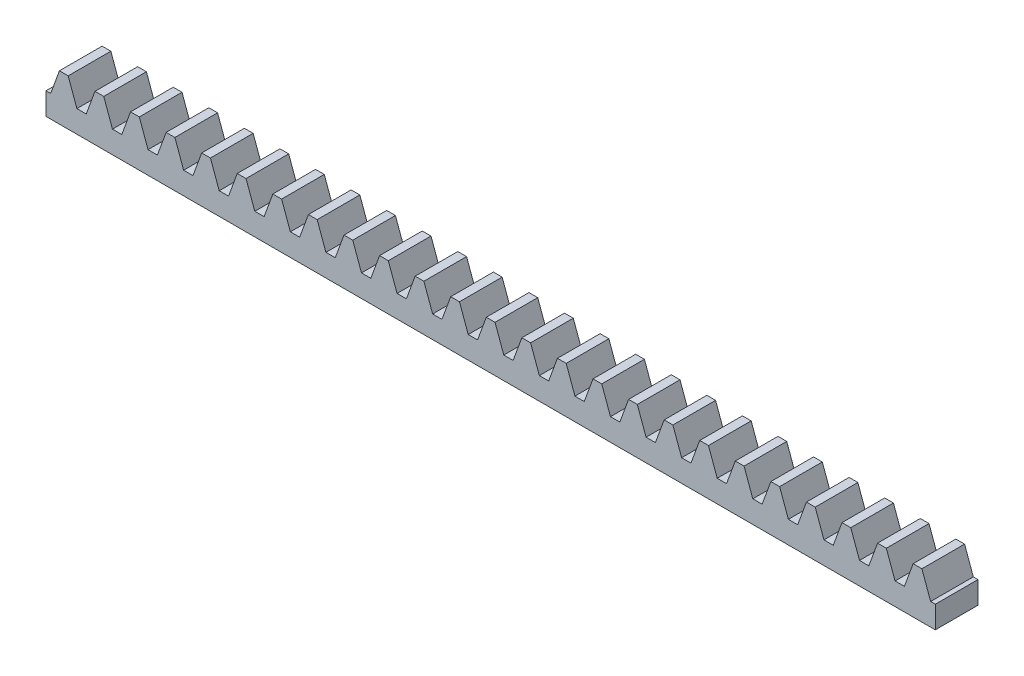
SolidWorks part; units mm, degrees
ref_plane "Plano frontal" through (0, 0, 0) normal (0, 0, 1) x (1, 0, 0)
ref_plane "Plano superior" through (0, 0, 0) normal (0, 1, 0) x (1, 0, 0)
ref_plane "Plano direito" through (0, 0, 0) normal (1, 0, 0) x (0, 0, -1)
sketch "Esboço1" plane through (0, 0, 0) normal (0, 0, 1) x (1, 0, 0)
  line L1 (0, 0) -> (250, 0)
  line L2 (0, 0) -> (0, 13)
  line L3 (0, 13) -> (250, 13)
  line L4 (250, 0) -> (250, 13)
  dimension "D1" = 13
  dimension "D2" = 250
extrude "Ressalto-extrusão1" add sketch "Esboço1" along normal blind 12
sketch "Esboço2" plane through (0, 0, 12) normal (0, 0, 1) x (1, 0, 0)
  line L0 (1.3123, 6.25) -> (-1.3123, 6.25)
  line L1 (3.7784, 13.0254) -> (1.3123, 6.25)
  line L2 (3.7784, 13.0254) -> (-3.7784, 13.0254)
  line L3 (-3.7784, 13.0254) -> (-1.3123, 6.25)
  line L4 (-2.6772, 10) -> (2.6772, 10) construction
  line L5 (0, 6.25) -> (0, 13.0254) construction
  line L6 (0, 0) -> (250, 0) construction
  line L8 (0, 13) -> (0, 0) construction
  dimension "D1" = 6.7754
  dimension "D2" = 7.5567
  dimension "D3" = 2.6246
  dimension "D4" = 3.75
  dimension "D5" = 10
  dimension "D6" = 20
  dimension "D7" = 3.0254
  dimension "D8" = 5.3544
extrude "Corte-extrusão1" cut sketch "Esboço2" against normal through all
pattern_linear "Padrão linear1" count 28 spacing 10 along (1, 0, 0) of "Corte-extrusão1"
